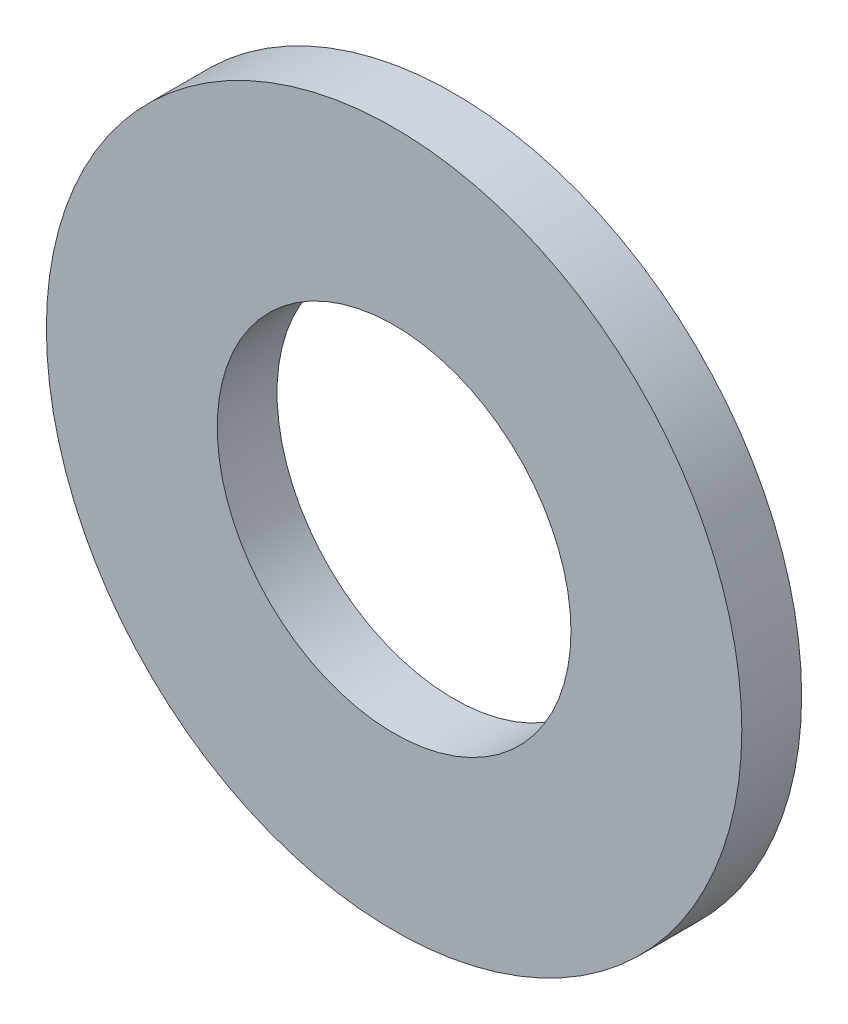
SolidWorks part; units mm, degrees
ref_plane "Front" through (0, 0, 0) normal (0, 0, 1) x (1, 0, 0)
ref_plane "Top" through (0, 0, 0) normal (0, 1, 0) x (1, 0, 0)
ref_plane "Right" through (0, 0, 0) normal (1, 0, 0) x (0, 0, -1)
sketch "Esquisse1" plane through (0, 0, 0) normal (0, 0, 1) x (1, 0, 0)
  circle A0 centre (0, 0) radius 10.35
  circle A1 centre (0, 0) radius 20.35
  dimension "D1" = 20.7
  dimension "D2" = 10
extrude "Boss.-Extru.1" add sketch "Esquisse1" along normal blind 3.5
